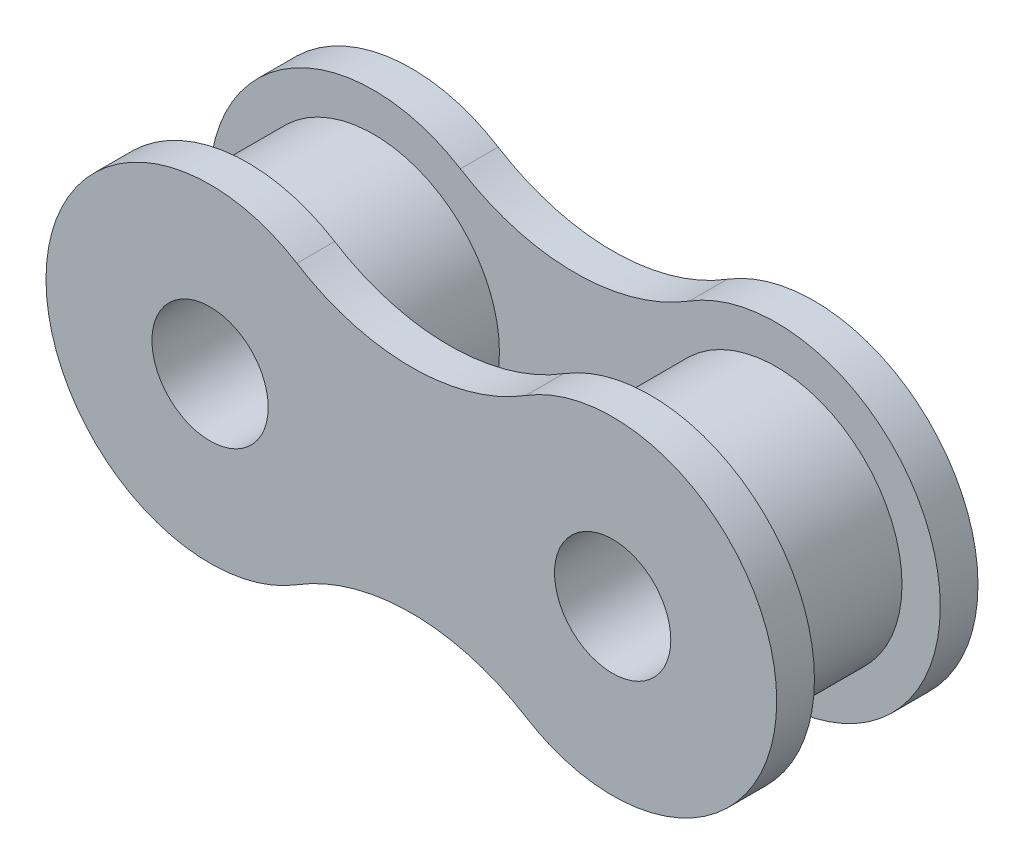
SolidWorks part; units mm, degrees
ref_plane "Front Plane" through (0, 0, 0) normal (0, 0, 1) x (1, 0, 0)
ref_plane "Top Plane" through (0, 0, 0) normal (0, 1, 0) x (1, 0, 0)
ref_plane "Right Plane" through (0, 0, 0) normal (1, 0, 0) x (0, 0, -1)
sketch "Sketch4" plane through (0, 0, -4.75) normal (0, 0, 1) x (1, 0, 0)
  circle A4 centre (-4, 0) radius 1.155 construction
  circle A5 centre (-4, 0) radius 1.155
  circle A7 centre (4, 0) radius 1.155
  arc A8 (-2.2751, 2.7663) -> (2.2751, 2.7663) centre (0, 6.4151) ccw
  arc A9 (-2.2751, 2.7663) -> (-2.2751, -2.7663) centre (-4, 0) ccw
  arc A10 (2.2751, -2.7663) -> (-2.2751, -2.7663) centre (0, -6.4151) ccw
  arc A11 (2.2751, -2.7663) -> (2.2751, 2.7663) centre (4, 0) ccw
  arc A12 (-2.2751, 2.7663) -> (2.2751, 2.7663) centre (0, 6.4151) ccw
  arc A13 (-2.2751, 2.7663) -> (-2.2751, -2.7663) centre (-4, 0) ccw
  arc A14 (2.2751, -2.7663) -> (-2.2751, -2.7663) centre (0, -6.4151) ccw
  arc A15 (2.2751, -2.7663) -> (2.2751, 2.7663) centre (4, 0) ccw
  circle A16 centre (4, 0) radius 1.155
  dimension "D1" = 0.3
  dimension "D2" = 0
extrude "Boss-Extrude1" add sketch "Sketch4" along normal blind 0.75
sketch "Sketch6" plane through (0, 0, -4) normal (0, 0, 1) x (1, 0, 0)
  circle A0 centre (4, 0) radius 1.155 construction
  circle A1 centre (4, 0) radius 1.155
  circle A2 centre (-4, 0) radius 1.155 construction
  circle A3 centre (-4, 0) radius 1.155
  circle A4 centre (-4, 0) radius 2.5
  circle A5 centre (4, 0) radius 2.5
  dimension "D1" = 5
extrude "Boss-Extrude2" add sketch "Sketch6" along normal up to surface (3.25 mm away)
ref_plane "Plane1" through (0, 0, -2.75) normal (0, 0, 1) x (1, 0, 0)
mirror "Mirror1" about plane through (0, 0, -2.75) normal (0, 0, 1) of "Boss-Extrude1"
